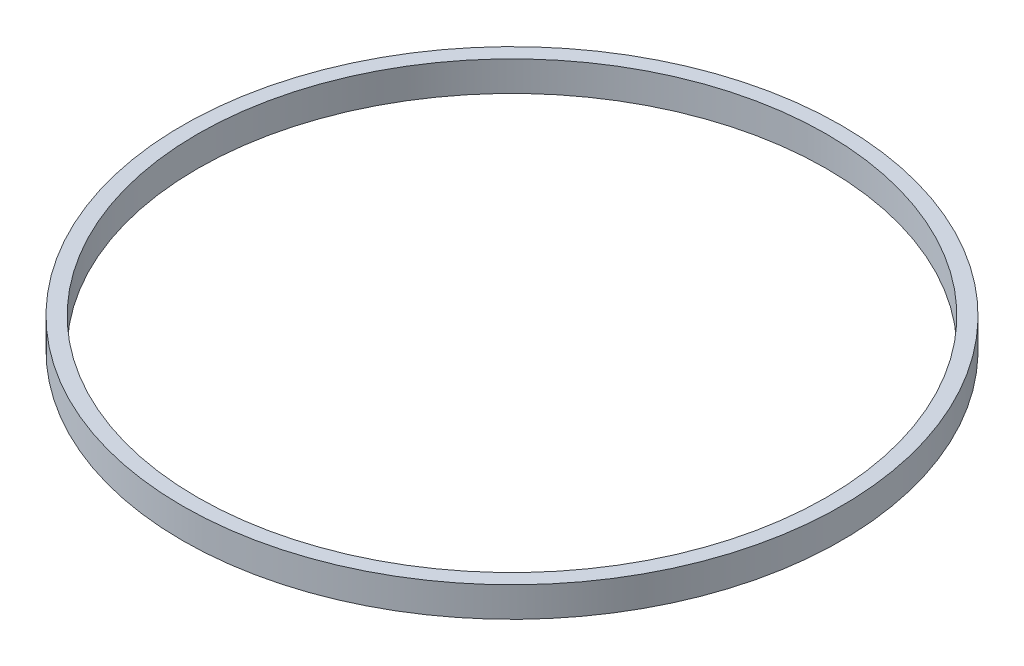
SolidWorks part; units mm, degrees
ref_plane "Front Plane" through (0, 0, 0) normal (0, 0, 1) x (1, 0, 0)
ref_plane "Top Plane" through (0, 0, 0) normal (0, 1, 0) x (1, 0, 0)
ref_plane "Right Plane" through (0, 0, 0) normal (1, 0, 0) x (0, 0, -1)
sketch "Sketch2" plane through (0, 0, 0) normal (0, 1, 0) x (1, 0, 0)
  circle A0 centre (0, 0) radius 33
  circle A1 centre (0, 0) radius 31.5
extrude "Boss-Extrude1" add sketch "Sketch2" along normal blind 3
